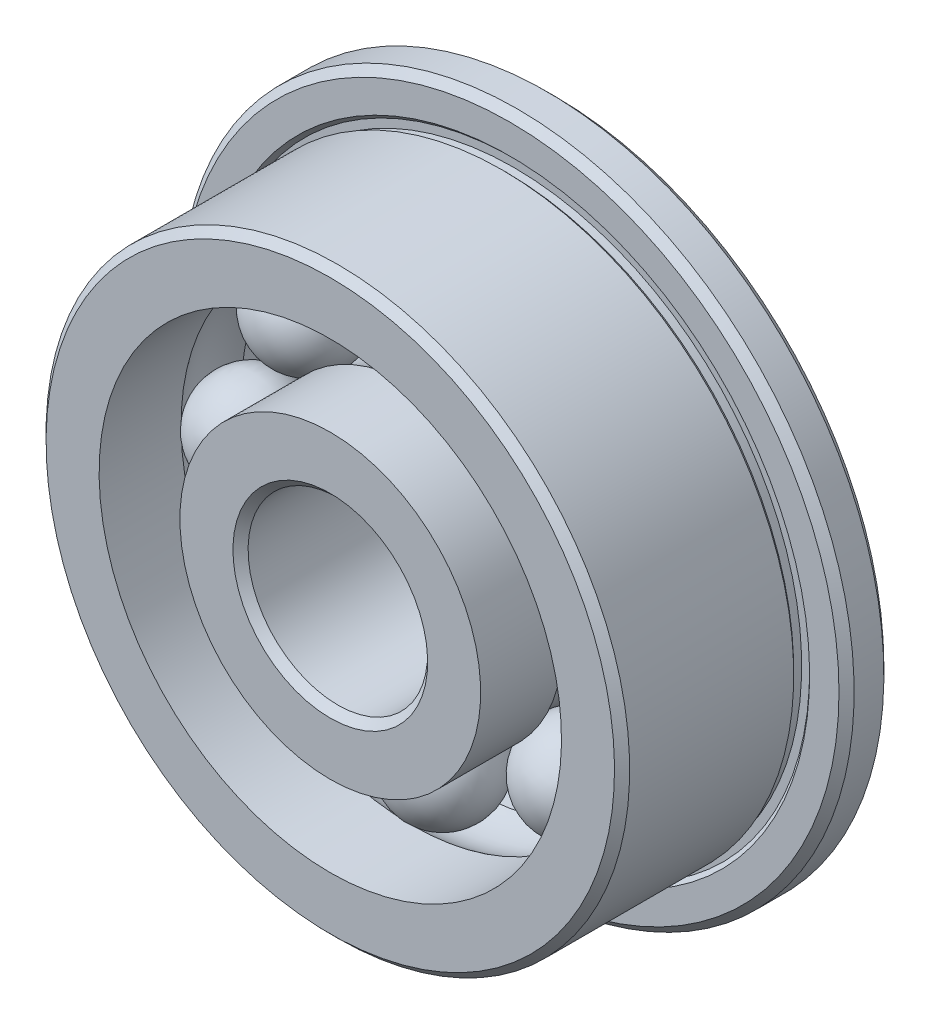
SolidWorks part; units mm, degrees
ref_plane "Front Plane" through (0, 0, 0) normal (0, 0, 1) x (1, 0, 0)
ref_plane "Top Plane" through (0, 0, 0) normal (0, 1, 0) x (1, 0, 0)
ref_plane "Right Plane" through (0, 0, 0) normal (1, 0, 0) x (0, 0, -1)
sketch "Sketch1" plane through (0, 0, 0) normal (1, 0, 0) x (0, 0, -1)
  line L0 (0, 6.5) -> (0, -6.5) construction
  line L1 (-2.5, 6.5) -> (2.5, 6.5) construction
  line L2 (0, 0) -> (2.5, 0) construction
  line L3 (2.5, 7.5) -> (2.5, -7.5) construction
  line L4 (2.5, -7.5) -> (1.5, -7.5) construction
  line L5 (2.5, 2) -> (0, 2) construction
  line L6 (2.5, 2) -> (2.5, -2) construction
  dimension "OD" = 13
  dimension "Width" = 5
  dimension "Flange Thickness" = 1
  dimension "ID" = 4
  dimension "Flange OD" = 15
sketch "Sketch2" plane through (0, 0, 0) normal (1, 0, 0) x (0, 0, -1)
  line L0 (2.5, 7.5) -> (1.5, 7.5)
  line L1 (1.5, 7.5) -> (1.5, 6.6768)
  line L2 (1.3232, 6.5) -> (-2.5, 6.5)
  line L3 (-2.5, 6.5) -> (-2.5, 5.15)
  line L4 (-2.5, 5.15) -> (-0.675, 5.15)
  line L5 (2.5, 7.5) -> (2.5, -7.5) construction
  line L6 (2.5, 5.15) -> (2.5, 7.5)
  line L7 (2.5, 2) -> (-2.5, 2)
  line L8 (-2.5, 2) -> (-2.5, 3.35)
  line L9 (-2.5, 3.35) -> (-0.675, 3.35)
  line L10 (2.5, 3.35) -> (2.5, 2)
  line L11 (0, 6.5) -> (0, 2) construction
  line L12 (-1.125, 4.25) -> (1.125, 4.25) construction
  line L13 (0.675, 5.15) -> (2.5, 5.15)
  line L14 (0.675, 3.35) -> (2.5, 3.35)
  line L15 (1.5, 6.6768) -> (1.5884, 6.5884)
  line L16 (1.5884, 6.5884) -> (1.5884, 6.4116)
  line L17 (1.5884, 6.4116) -> (1.4116, 6.4116)
  line L18 (1.4116, 6.4116) -> (1.3232, 6.5)
  line L19 (1.5, 6.5) -> (1.5884, 6.4116) construction
  line L20 (1.5884, 6.5884) -> (1.4116, 6.4116) construction
  line L21 (1.3232, 6.5) -> (1.5, 6.5) construction
  line L22 (1.5, 6.5) -> (1.5, 6.6768) construction
  circle A0 centre (0, 4.25) radius 1.125 construction
  arc A1 (-0.675, 5.15) -> (0.675, 5.15) centre (0, 4.25) cw
  arc A2 (-0.675, 3.35) -> (0.675, 3.35) centre (0, 4.25) ccw
  dimension "D1" = 4.5
  dimension "Ball Dia." = 2.25
  dimension "D2" = 135
  dimension "D3" = 0.25
  dimension "D4" = 1.8
  dimension "Race Thikness" = 1.35
revolve "Revolve1" add sketch "Sketch2" angle 360 about L2
fillet "Fillet1" radius 0.1688 3 edges at (0, -7.5, -2.5) (0, -7.5, -1.5) (0, -6.5, 2.5) profile chamfer
sketch "Sketch3" plane through (0, 0, 0) normal (0, 0, 1) x (1, 0, 0)
  line L0 (-2, 0) -> (2, 0) construction
  line L1 (-6.5, 0) -> (6.5, 0) construction
  point P5 (0, 0)
  dimension "ID2" = 4
  dimension "OD2" = 13
fillet "Fillet2" radius 0.1688 2 edges at (0, -2, -2.5) (0, -2, 2.5) profile chamfer
sketch "Sketch7" plane through (0, 0, 0) normal (0, 0, 1) x (1, 0, 0)
  line L0 (0, 5.375) -> (0, 3.125)
  line L1 (0, 7.5) -> (0, -7.5) construction
  line L2 (-1.4754, 5.375) -> (0, 0) construction
  line L3 (0, 0) -> (1.4754, 5.375) construction
  line L4 (1.4754, 5.375) -> (-1.4754, 5.375) construction
  circle A0 centre (0, 4.25) radius 1.125 construction
  circle A1 centre (0, 0) radius 5.375 construction
  circle A2 centre (0, 0) radius 3.125 construction
  arc A4 (0, 5.375) -> (0, 3.125) centre (0, 4.25) ccw
  dimension "D1" = 30.699
revolve "Revolve3" add sketch "Sketch7" angle 360 about L0
pattern_circular "CirPattern3" count 8 over 360 about axis through (0, 0, 0) along (0, 0, 1) of bodies 107
sketch "Sketch8" plane through (0, 0, 0) normal (1, 0, 0) x (0, 0, -1)
  line L0 (-2.5, 6.5) -> (2.5, 6.5) construction
  line L1 (2.5, 6.5) -> (2.5, 7.5) construction
  line L2 (-2.5, -6.5) -> (2.5, -6.5) construction
  line L3 (2.5, 7.5) -> (2.5, -7.5) construction
  dimension "D1" = 13
equation "\"Ball Dia.@Sketch2\" = ( \"OD@Sketch1\" - \"ID@Sketch1\" ) * .25"
equation "\"D3@Sketch2\"=\"Flange Thickness@Sketch1\"/4"
equation "\"D1@Fillet1\" = \"Race Thikness@Sketch2\" / 8"
equation "\"ID2@Sketch3\" = \"ID@Sketch1\""
equation "\"OD2@Sketch3\" = \"OD@Sketch1\""
equation "\"D1@Fillet2\" = \"Race Thikness@Sketch2\" / 8"
equation "\"D1@CirPattern3\"=360/\"D1@Sketch7\"-4"
equation "\"D4@Sketch2\" = ( \"OD@Sketch1\" - \"ID@Sketch1\" ) * .2"
